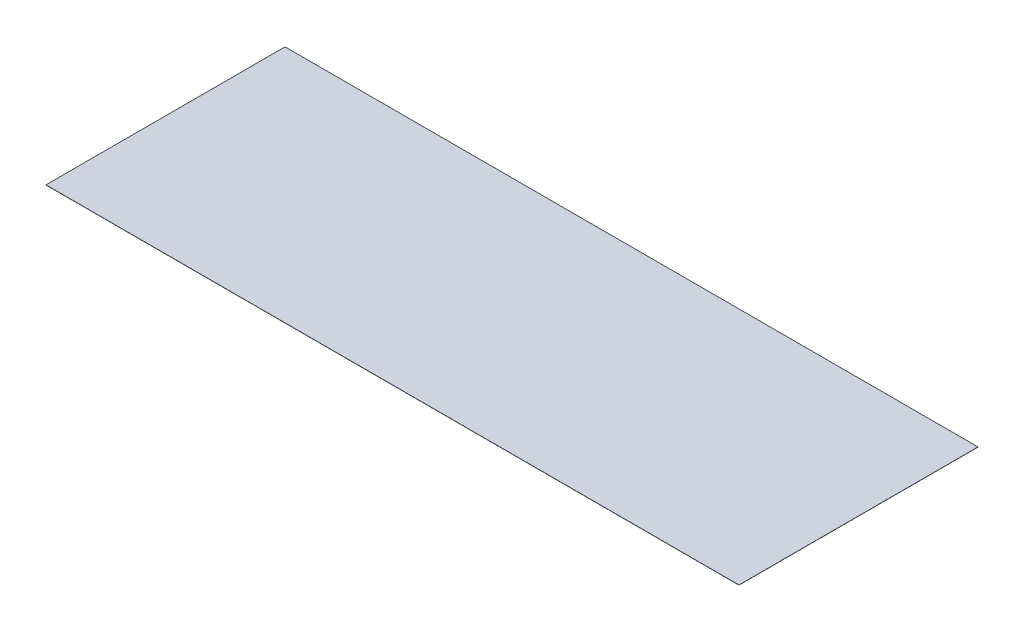
SolidWorks part; units mm, degrees
material "PE High Density Film"
ref_plane "Front Plane" through (0, 0, 0) normal (0, 0, 1) x (1, 0, 0)
ref_plane "Top Plane" through (0, 0, 0) normal (0, 1, 0) x (1, 0, 0)
ref_plane "Right Plane" through (0, 0, 0) normal (1, 0, 0) x (0, 0, -1)
sketch "Sketch1" plane through (0, 0, 0) normal (0, 1, 0) x (1, 0, 0)
  line L1 (-3048, -1051.306) -> (3048, -1051.306)
  line L2 (-3048, -1051.306) -> (-3048, 1051.306)
  line L3 (-3048, 1051.306) -> (3048, 1051.306)
  line L4 (3048, -1051.306) -> (3048, 1051.306)
  line L5 (-3048, -1051.306) -> (3048, 1051.306) construction
  line L6 (-3048, 1051.306) -> (3048, -1051.306) construction
  point P0 (0, 0)
  dimension "D1" = 2102.612
  dimension "D2" = 6096
extrude "Boss-Extrude1" add sketch "Sketch1" along normal blind 1.5875
